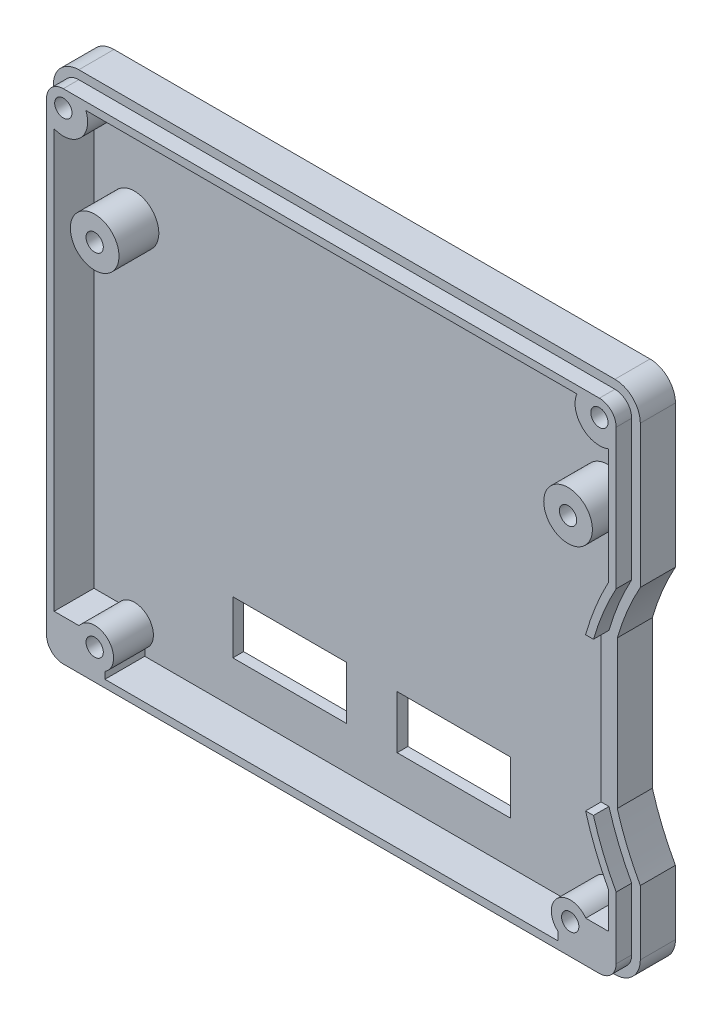
SolidWorks part; units mm, degrees
material "ABS"
ref_plane "Front Plane" through (0, 0, 0) normal (0, 0, 1) x (1, 0, 0)
ref_plane "Top Plane" through (0, 0, 0) normal (0, 1, 0) x (1, 0, 0)
ref_plane "Right Plane" through (0, 0, 0) normal (1, 0, 0) x (0, 0, -1)
sketch "Sketch1" plane through (0, 0, 0) normal (0, 0, 1) x (1, 0, 0)
  line L1 (-54.3, -47.7) -> (54.3, -47.7)
  line L2 (-54.3, -47.7) -> (-54.3, 47.7)
  line L3 (-54.3, 47.7) -> (54.3, 47.7)
  line L4 (54.3, -47.7) -> (54.3, 47.7)
  line L5 (-54.3, -47.7) -> (54.3, 47.7) construction
  line L6 (-54.3, 47.7) -> (54.3, -47.7) construction
  point P0 (0, 0)
  dimension "D1" = 108.6
  dimension "D2" = 95.4
extrude "Boss-Extrude1" add sketch "Sketch1" along normal blind 6.5
fillet "Fillet1" radius 4.7 4 edges at (-54.3, 47.7, 3.25) (-54.3, -47.7, 3.25) (54.3, -47.7, 3.25) (54.3, 47.7, 3.25)
sketch "Sketch4" plane through (0, 0, 6.5) normal (0, 0, 1) x (1, 0, 0)
  line L0 (54.3, -43) -> (54.3, 43) construction
  line L1 (-49.6, -47.7) -> (49.6, -47.7) construction
  line L2 (50.037, 6.4675) -> (50.037, -20.8702)
  arc A0 (50.037, -20.8702) -> (50.037, 6.4675) centre (97.196, -7.2014) ccw
  dimension "D1" = 98.2
  dimension "D2" = 42.896
  dimension "D3" = 40.4986
  dimension "D4" = 4.263
extrude "Cut-Extrude2" cut sketch "Sketch4" against normal through all
shell "Shell1" thickness 3
sketch "Sketch3" plane through (0, 0, 6.5) normal (0, 0, 1) x (1, 0, 0)
  line L0 (-49.6, -47.7) -> (49.6, -47.7) construction
  line L1 (-25.6, -27) -> (-4.6, -27)
  line L2 (-25.6, -27) -> (-25.6, -36.8)
  line L3 (-25.6, -36.8) -> (-4.6, -36.8)
  line L4 (-4.6, -27) -> (-4.6, -36.8)
  line L5 (4.8, -27) -> (25.8, -27)
  line L6 (4.8, -27) -> (4.8, -36.8)
  line L7 (4.8, -36.8) -> (25.8, -36.8)
  line L8 (25.8, -27) -> (25.8, -36.8)
  line L9 (-54.3, 43) -> (-54.3, -43) construction
  dimension "D1" = 21
  dimension "D2" = 9.4
  dimension "D3" = 9.8
  dimension "D4" = 10.9
  dimension "D5" = 28.7
extrude "Cut-Extrude1" cut sketch "Sketch3" against normal through all
sketch "Sketch5" plane through (0, 0, 6.5) normal (0, 0, 1) x (1, 0, 0)
  line L0 (-49.6, -47.7) -> (49.6, -47.7) construction
  line L1 (-54.3, 43) -> (-54.3, -43) construction
  line L2 (49.6, 47.7) -> (-49.6, 47.7) construction
  line L3 (54.3, 16.6888) -> (54.3, 43) construction
  line L4 (54.3, -43) -> (54.3, -31.0915) construction
  line L5 (-49.6, -47.7) -> (49.6, -47.7) construction
  line L6 (-54.3, 43) -> (-54.3, -43) construction
  line L7 (49.6, 47.7) -> (-49.6, 47.7) construction
  line L8 (54.3, 16.6888) -> (54.3, 43) construction
  line L9 (54.3, -43) -> (54.3, -31.0915) construction
  line L10 (52.7, 17.1008) -> (52.7, 43)
  line L11 (49.6, 46.1) -> (-49.6, 46.1)
  line L12 (-52.7, 43) -> (-52.7, -43)
  line L13 (-49.6, -46.1) -> (49.6, -46.1)
  line L14 (52.7, -43) -> (52.7, -31.5035)
  line L15 (-49.6, -44.7) -> (49.6, -44.7) construction
  line L16 (-51.3, 43) -> (-51.3, -43) construction
  line L17 (49.6, 44.7) -> (-49.6, 44.7) construction
  line L18 (51.3, 17.4556) -> (51.3, 43) construction
  line L19 (51.3, -43) -> (51.3, -31.8583) construction
  line L20 (-49.6, -44.7) -> (49.6, -44.7)
  line L21 (-51.3, 43) -> (-51.3, -43)
  line L22 (49.6, 44.7) -> (-49.6, 44.7)
  line L23 (51.3, 17.4556) -> (51.3, 43)
  line L24 (51.3, -43) -> (51.3, -31.8583)
  line L25 (48.5002, 6.9129) -> (47.0443, 6.9129)
  line L26 (48.5002, -21.3156) -> (47.0443, -21.3156)
  arc A0 (-54.3, -43) -> (-49.6, -47.7) centre (-49.6, -43) ccw construction
  arc A1 (-49.6, 47.7) -> (-54.3, 43) centre (-49.6, 43) ccw construction
  arc A2 (54.3, 43) -> (49.6, 47.7) centre (49.6, 43) ccw construction
  arc A3 (49.6, -47.7) -> (54.3, -43) centre (49.6, -43) ccw construction
  arc A4 (-54.3, -43) -> (-49.6, -47.7) centre (-49.6, -43) ccw construction
  arc A5 (-49.6, 47.7) -> (-54.3, 43) centre (-49.6, 43) ccw construction
  arc A6 (54.3, 43) -> (49.6, 47.7) centre (49.6, 43) ccw construction
  arc A7 (49.6, -47.7) -> (54.3, -43) centre (49.6, -43) ccw construction
  arc A8 (50.037, -20.8702) -> (54.3, -31.0915) centre (97.196, -7.2014) ccw construction
  arc A9 (50.037, -20.8702) -> (54.3, -31.0915) centre (97.196, -7.2014) ccw construction
  arc A10 (54.3, 16.6888) -> (50.037, 6.4675) centre (97.196, -7.2014) ccw construction
  arc A11 (54.3, 16.6888) -> (50.037, 6.4675) centre (97.196, -7.2014) ccw construction
  arc A12 (52.7, 17.1008) -> (48.5002, 6.9129) centre (97.196, -7.2014) ccw
  arc A13 (52.7, 43) -> (49.6, 46.1) centre (49.6, 43) ccw
  arc A14 (-49.6, 46.1) -> (-52.7, 43) centre (-49.6, 43) ccw
  arc A15 (-52.7, -43) -> (-49.6, -46.1) centre (-49.6, -43) ccw
  arc A16 (49.6, -46.1) -> (52.7, -43) centre (49.6, -43) ccw
  arc A17 (48.5002, -21.3156) -> (52.7, -31.5035) centre (97.196, -7.2014) ccw
  arc A18 (-51.3, -43) -> (-49.6, -44.7) centre (-49.6, -43) ccw construction
  arc A19 (-49.6, 44.7) -> (-51.3, 43) centre (-49.6, 43) ccw construction
  arc A20 (51.3, 43) -> (49.6, 44.7) centre (49.6, 43) ccw construction
  arc A21 (49.6, -44.7) -> (51.3, -43) centre (49.6, -43) ccw construction
  arc A22 (-51.3, -43) -> (-49.6, -44.7) centre (-49.6, -43) ccw
  arc A23 (-49.6, 44.7) -> (-51.3, 43) centre (-49.6, 43) ccw
  arc A24 (51.3, 43) -> (49.6, 44.7) centre (49.6, 43) ccw
  arc A25 (49.6, -44.7) -> (51.3, -43) centre (49.6, -43) ccw
  arc A26 (47.037, -21.2897) -> (51.3, -31.8583) centre (97.196, -7.2014) ccw construction
  arc A27 (47.0443, -21.3156) -> (51.3, -31.8583) centre (97.196, -7.2014) ccw
  arc A28 (51.3, 17.4556) -> (47.037, 6.887) centre (97.196, -7.2014) ccw construction
  arc A29 (51.3, 17.4556) -> (47.0443, 6.9129) centre (97.196, -7.2014) ccw
  dimension "D1" = 1.6
extrude "Boss-Extrude2" add sketch "Sketch5" along normal blind 2.87
sketch "Sketch6" plane through (0, 0, 2) normal (0, 0, 1) x (1, 0, 0)
  line L0 (-54.3, 43) -> (-54.3, -43) construction
  line L1 (49.6, 47.7) -> (-49.6, 47.7) construction
  line L2 (-49.6, -47.7) -> (49.6, -47.7) construction
  line L3 (54.3, -43) -> (54.3, -31.0915) construction
  circle A0 centre (-49.6, 43) radius 1.6
  circle A1 centre (-43.8, 24.4) radius 1.6
  circle A2 centre (43.8, 24.4) radius 1.6
  circle A3 centre (49.6, 43) radius 1.6
  circle A4 centre (49.6, -43) radius 1.6
  circle A5 centre (44.2, -40.5) radius 1.6
  circle A6 centre (-49.6, -43) radius 1.6
  circle A7 centre (-43.8, -40.5) radius 1.6
  dimension "D1" = 3.2
  dimension "D2" = 4.7
  dimension "D3" = 4.7
  dimension "D4" = 4.7
  dimension "D5" = 4.7
  dimension "D6" = 87.6
  dimension "D7" = 18.6
  dimension "D8" = 5.8
  dimension "D9" = 64.9
  dimension "D10" = 88
extrude "Cut-Extrude3" cut sketch "Sketch6" against normal through all
sketch "Sketch7" plane through (0, 0, 2) normal (0, 0, 1) x (1, 0, 0)
  line L0 (47.0723, -38.5) -> (51.3, -38.5)
  line L1 (41.9, -43.1382) -> (41.9, -44.7)
  line L2 (-49.6, -44.7) -> (49.6, -44.7) construction
  line L3 (51.3, -43) -> (51.3, -31.8583) construction
  line L4 (-49.6, -44.7) -> (-41.9, -44.7)
  line L5 (51.3, -43) -> (51.3, -38.5)
  line L6 (41.9, -44.7) -> (49.6, -44.7)
  line L7 (54.3, -43) -> (54.3, -31.0915) construction
  line L8 (-49.6, -47.7) -> (49.6, -47.7) construction
  line L9 (-51.3, -43) -> (-51.3, 43) construction
  line L10 (-49.6, 44.7) -> (49.6, 44.7) construction
  line L11 (-51.3, -43) -> (-51.3, -38.5)
  line L12 (-49.6, 44.7) -> (-45.4335, 44.7)
  line L13 (-51.3, 38.8335) -> (-51.3, 43)
  line L14 (45.4335, 44.7) -> (49.6, 44.7)
  line L15 (51.3, 43) -> (51.3, 17.4556) construction
  line L16 (51.3, 43) -> (51.3, 38.8335)
  line L17 (-51.3, -38.5) -> (-46.6723, -38.5)
  line L18 (-41.9, -44.7) -> (-41.9, -43.4394)
  line L19 (-54.3, 43) -> (-54.3, -43) construction
  circle A0 centre (-43.8, 24.4) radius 4.5
  circle A1 centre (43.8, 24.4) radius 4.5
  arc A2 (-51.3, 38.8335) -> (-45.4335, 44.7) centre (-49.6, 43) ccw
  arc A3 (45.4335, 44.7) -> (51.3, 38.8335) centre (49.6, 43) ccw
  arc A4 (-51.3, -43) -> (-49.6, -44.7) centre (-49.6, -43) ccw construction
  arc A5 (-49.6, 44.7) -> (-51.3, 43) centre (-49.6, 43) ccw construction
  arc A6 (47.0723, -38.5) -> (41.9, -43.1382) centre (44.2, -40.5) ccw
  arc A8 (49.6, -44.7) -> (51.3, -43) centre (49.6, -43) ccw construction
  arc A9 (49.6, -44.7) -> (51.3, -43) centre (49.6, -43) ccw
  arc A10 (-49.6, 44.7) -> (-51.3, 43) centre (-49.6, 43) ccw
  arc A11 (51.3, 43) -> (49.6, 44.7) centre (49.6, 43) ccw construction
  arc A12 (51.3, 43) -> (49.6, 44.7) centre (49.6, 43) ccw
  arc A13 (-41.9, -43.4394) -> (-46.6723, -38.5) centre (-43.8, -40.5) ccw
  arc A14 (-51.3, -43) -> (-49.6, -44.7) centre (-49.6, -43) ccw
  circle A15 centre (-43.8, -40.5) radius 1.6 construction
  circle A16 centre (-43.8, -40.5) radius 1.6
  circle A17 centre (-43.8, 24.4) radius 1.6 construction
  circle A18 centre (-49.6, 43) radius 1.6 construction
  circle A19 centre (-43.8, 24.4) radius 1.6
  circle A20 centre (-49.6, 43) radius 1.6
  circle A21 centre (49.6, 43) radius 1.6 construction
  circle A22 centre (43.8, 24.4) radius 1.6 construction
  circle A23 centre (44.2, -40.5) radius 1.6 construction
  circle A24 centre (49.6, 43) radius 1.6
  circle A25 centre (43.8, 24.4) radius 1.6
  circle A26 centre (44.2, -40.5) radius 1.6
  dimension "D3" = 3.5
  dimension "D4" = 9
  dimension "D1" = 12.4
  dimension "D2" = 9.2
  dimension "D5" = 12.4
extrude "Boss-Extrude3" add sketch "Sketch7" along normal up to surface (7.37 mm away) up to face at (16.5815, -2.4004, 9.37)
